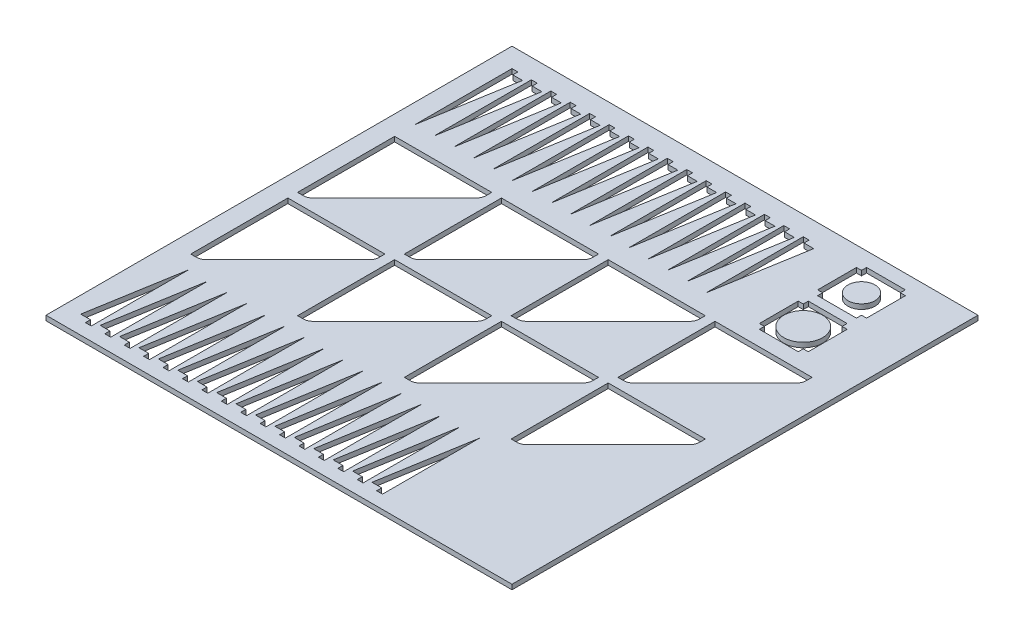
SolidWorks part; units mm, degrees
ref_plane "Front Plane" through (0, 0, 0) normal (0, 0, 1) x (1, 0, 0)
ref_plane "Top Plane" through (0, 0, 0) normal (0, 1, 0) x (1, 0, 0)
ref_plane "Right Plane" through (0, 0, 0) normal (1, 0, 0) x (0, 0, -1)
sketch "Sketch2" plane through (0, 0, 0) normal (0, 1, 0) x (1, 0, 0)
  line L6 (-209.1635, -277.3688) -> (95.6365, -277.3688)
  line L7 (-209.1635, -277.3688) -> (-209.1635, 27.4312)
  line L8 (95.6365, -277.3688) -> (95.6365, 27.4312)
  line L9 (-209.1635, 27.4312) -> (95.6365, 27.4312)
  point P0 (0, 0)
  dimension "D5" = 304.8
  dimension "D6" = 304.8
extrude "Boss-Extrude1" add sketch "Sketch2" along normal blind 3.175
sketch "Sketch3" plane through (0, 3.175, 0) normal (0, 1, 0) x (1, 0, 0)
  line L0 (-196.4635, 14.7312) -> (-196.4635, -48.7688)
  line L1 (-196.4635, -48.7688) -> (-186.3035, 11.4292)
  line L2 (-186.3035, 11.4292) -> (-192.6535, 11.4292)
  line L3 (-192.6535, 11.4292) -> (-192.6535, 14.7312)
  line L4 (-192.6535, 14.7312) -> (-196.4635, 14.7312)
  line L5 (-209.1635, 27.4312) -> (-209.1635, -277.3688) construction
  line L6 (95.6365, 27.4312) -> (-209.1635, 27.4312) construction
  line L7 (-179.9535, 14.7312) -> (-183.7635, 14.7312)
  line L8 (-183.7635, 14.7312) -> (-183.7635, -48.7688)
  line L9 (-183.7635, -48.7688) -> (-173.6035, 11.4292)
  line L10 (-173.6035, 11.4292) -> (-179.9535, 11.4292)
  line L11 (-179.9535, 11.4292) -> (-179.9535, 14.7312)
  line L12 (-167.2535, 14.7312) -> (-171.0635, 14.7312)
  line L13 (-171.0635, 14.7312) -> (-171.0635, -48.7688)
  line L14 (-171.0635, -48.7688) -> (-160.9035, 11.4292)
  line L15 (-160.9035, 11.4292) -> (-167.2535, 11.4292)
  line L16 (-167.2535, 11.4292) -> (-167.2535, 14.7312)
  line L17 (-154.5535, 14.7312) -> (-158.3635, 14.7312)
  line L18 (-158.3635, 14.7312) -> (-158.3635, -48.7688)
  line L19 (-158.3635, -48.7688) -> (-148.2035, 11.4292)
  line L20 (-148.2035, 11.4292) -> (-154.5535, 11.4292)
  line L21 (-154.5535, 11.4292) -> (-154.5535, 14.7312)
  line L22 (-141.8535, 14.7312) -> (-145.6635, 14.7312)
  line L23 (-145.6635, 14.7312) -> (-145.6635, -48.7688)
  line L24 (-145.6635, -48.7688) -> (-135.5035, 11.4292)
  line L25 (-135.5035, 11.4292) -> (-141.8535, 11.4292)
  line L26 (-141.8535, 11.4292) -> (-141.8535, 14.7312)
  line L27 (-129.1535, 14.7312) -> (-132.9635, 14.7312)
  line L28 (-132.9635, 14.7312) -> (-132.9635, -48.7688)
  line L29 (-132.9635, -48.7688) -> (-122.8035, 11.4292)
  line L30 (-122.8035, 11.4292) -> (-129.1535, 11.4292)
  line L31 (-129.1535, 11.4292) -> (-129.1535, 14.7312)
  line L32 (-116.4535, 14.7312) -> (-120.2635, 14.7312)
  line L33 (-120.2635, 14.7312) -> (-120.2635, -48.7688)
  line L34 (-120.2635, -48.7688) -> (-110.1035, 11.4292)
  line L35 (-110.1035, 11.4292) -> (-116.4535, 11.4292)
  line L36 (-116.4535, 11.4292) -> (-116.4535, 14.7312)
  line L37 (-103.7535, 14.7312) -> (-107.5635, 14.7312)
  line L38 (-107.5635, 14.7312) -> (-107.5635, -48.7688)
  line L39 (-107.5635, -48.7688) -> (-97.4035, 11.4292)
  line L40 (-97.4035, 11.4292) -> (-103.7535, 11.4292)
  line L41 (-103.7535, 11.4292) -> (-103.7535, 14.7312)
  line L42 (-91.0535, 14.7312) -> (-94.8635, 14.7312)
  line L43 (-94.8635, 14.7312) -> (-94.8635, -48.7688)
  line L44 (-94.8635, -48.7688) -> (-84.7035, 11.4292)
  line L45 (-84.7035, 11.4292) -> (-91.0535, 11.4292)
  line L46 (-91.0535, 11.4292) -> (-91.0535, 14.7312)
  line L47 (-78.3535, 14.7312) -> (-82.1635, 14.7312)
  line L48 (-82.1635, 14.7312) -> (-82.1635, -48.7688)
  line L49 (-82.1635, -48.7688) -> (-72.0035, 11.4292)
  line L50 (-72.0035, 11.4292) -> (-78.3535, 11.4292)
  line L51 (-78.3535, 11.4292) -> (-78.3535, 14.7312)
  line L52 (-65.6535, 14.7312) -> (-69.4635, 14.7312)
  line L53 (-69.4635, 14.7312) -> (-69.4635, -48.7688)
  line L54 (-69.4635, -48.7688) -> (-59.3035, 11.4292)
  line L55 (-59.3035, 11.4292) -> (-65.6535, 11.4292)
  line L56 (-65.6535, 11.4292) -> (-65.6535, 14.7312)
  line L57 (-52.9535, 14.7312) -> (-56.7635, 14.7312)
  line L58 (-56.7635, 14.7312) -> (-56.7635, -48.7688)
  line L59 (-56.7635, -48.7688) -> (-46.6035, 11.4292)
  line L60 (-46.6035, 11.4292) -> (-52.9535, 11.4292)
  line L61 (-52.9535, 11.4292) -> (-52.9535, 14.7312)
  line L62 (-40.2535, 14.7312) -> (-44.0635, 14.7312)
  line L63 (-44.0635, 14.7312) -> (-44.0635, -48.7688)
  line L64 (-44.0635, -48.7688) -> (-33.9035, 11.4292)
  line L65 (-33.9035, 11.4292) -> (-40.2535, 11.4292)
  line L66 (-40.2535, 11.4292) -> (-40.2535, 14.7312)
  line L67 (-27.5535, 14.7312) -> (-31.3635, 14.7312)
  line L68 (-31.3635, 14.7312) -> (-31.3635, -48.7688)
  line L69 (-31.3635, -48.7688) -> (-21.2035, 11.4292)
  line L70 (-21.2035, 11.4292) -> (-27.5535, 11.4292)
  line L71 (-27.5535, 11.4292) -> (-27.5535, 14.7312)
  line L72 (-14.8535, 14.7312) -> (-18.6635, 14.7312)
  line L73 (-18.6635, 14.7312) -> (-18.6635, -48.7688)
  line L74 (-18.6635, -48.7688) -> (-8.5035, 11.4292)
  line L75 (-8.5035, 11.4292) -> (-14.8535, 11.4292)
  line L76 (-14.8535, 11.4292) -> (-14.8535, 14.7312)
  line L77 (-2.1535, 14.7312) -> (-5.9635, 14.7312)
  line L78 (-5.9635, 14.7312) -> (-5.9635, -48.7688)
  line L79 (-5.9635, -48.7688) -> (4.1965, 11.4292)
  line L80 (4.1965, 11.4292) -> (-2.1535, 11.4292)
  line L81 (-2.1535, 11.4292) -> (-2.1535, 14.7312)
  line L326 (-133.5339, -68.3803) -> (-132.9635, -68.3803)
  line L328 (32.1365, 14.7312) -> (28.8345, 14.7312)
  line L329 (32.1365, -10.6688) -> (28.8345, -10.6688)
  line L330 (28.8345, 14.7312) -> (28.8345, -10.6688)
  line L331 (-196.4635, -62.0303) -> (-132.9635, -62.0303)
  line L333 (32.1365, 14.7312) -> (32.1365, 18.0332)
  line L334 (57.5365, 14.7312) -> (57.5365, 18.0332)
  line L335 (32.1365, 18.0332) -> (57.5365, 18.0332)
  line L336 (32.1365, -10.6688) -> (32.1365, -13.9708)
  line L337 (57.5365, -13.9708) -> (32.1365, -13.9708)
  line L338 (57.5365, -10.6688) -> (57.5365, -13.9708)
  line L339 (-196.4635, -62.0303) -> (-196.4635, -125.5303)
  line L340 (57.5365, 14.7312) -> (60.8385, 14.7312)
  line L341 (60.8385, -10.6688) -> (60.8385, 14.7312)
  line L342 (57.5365, -10.6688) -> (60.8385, -10.6688)
  line L343 (-196.4635, -125.5303) -> (-192.7438, -125.5303)
  line L352 (57.5365, -52.0708) -> (32.1365, -52.0708)
  line L353 (57.5365, -52.0708) -> (57.5365, -48.7688)
  line L354 (32.1365, -20.0668) -> (57.5365, -20.0668)
  line L355 (60.8385, -48.7688) -> (60.8385, -23.3688)
  line L356 (57.5365, -48.7688) -> (60.8385, -48.7688)
  line L357 (-132.9635, -62.0303) -> (-132.9635, -65.7501)
  line L359 (32.1365, -23.3688) -> (32.1365, -20.0668)
  line L361 (-190.1135, -124.96) -> (-190.1135, -125.5303)
  line L362 (32.1365, -48.7688) -> (28.8345, -48.7688)
  line L363 (32.1365, -48.7688) -> (32.1365, -52.0708)
  line L364 (-190.1135, -68.3803) -> (-139.3135, -68.3803) construction
  line L365 (-10.4536, -205.1954) -> (-20.6136, -265.3934)
  line L366 (-190.1135, -68.3803) -> (-190.1135, -119.1803) construction
  line L367 (-134.8234, -70.2402) -> (-188.2536, -123.6705)
  line L368 (-196.4635, -125.5303) -> (-132.9635, -125.5303) construction
  line L369 (-132.9635, -62.0303) -> (-132.9635, -125.5303) construction
  line L370 (-126.6135, -125.5303) -> (-122.8938, -125.5303)
  line L371 (57.5365, -23.3688) -> (60.8385, -23.3688)
  line L372 (-126.6135, -62.0303) -> (-126.6135, -125.5303)
  line L373 (-126.6135, -62.0303) -> (-63.1135, -62.0303)
  line L374 (32.1365, -23.3688) -> (28.8345, -23.3688)
  line L375 (57.5365, -23.3688) -> (57.5365, -20.0668)
  line L376 (-63.1135, -62.0303) -> (-63.1135, -65.7501)
  line L377 (28.8345, -23.3688) -> (28.8345, -48.7688)
  line L378 (-139.3135, -68.3803) -> (-139.3135, -119.1803) construction
  line L379 (-190.1135, -119.1803) -> (-139.3135, -119.1803) construction
  line L380 (-64.9734, -70.2402) -> (-118.4036, -123.6705)
  line L381 (-56.7635, -125.5303) -> (-53.0438, -125.5303)
  line L382 (-56.7635, -62.0303) -> (-56.7635, -125.5303)
  line L383 (-56.7635, -62.0303) -> (6.7365, -62.0303)
  line L384 (6.7365, -62.0303) -> (6.7365, -65.7501)
  line L385 (4.8766, -70.2402) -> (-48.5536, -123.6705)
  line L386 (13.0865, -125.5303) -> (16.8062, -125.5303)
  line L387 (13.0865, -62.0303) -> (13.0865, -125.5303)
  line L388 (13.0865, -62.0303) -> (76.5865, -62.0303)
  line L389 (76.5865, -62.0303) -> (76.5865, -65.7501)
  line L390 (74.7266, -70.2402) -> (21.2964, -123.6705)
  line L391 (76.5865, -131.8803) -> (76.5865, -135.6001)
  line L392 (-134.8234, -140.0902) -> (-188.2536, -193.5205)
  line L393 (-126.6135, -131.8803) -> (-63.1135, -131.8803)
  line L394 (-56.7635, -195.3803) -> (-53.0438, -195.3803)
  line L395 (-126.6135, -195.3803) -> (-122.8938, -195.3803)
  line L396 (-126.6135, -131.8803) -> (-126.6135, -195.3803)
  line L397 (-56.7635, -131.8803) -> (-56.7635, -195.3803)
  line L398 (13.0865, -195.3803) -> (16.8062, -195.3803)
  line L399 (-63.1135, -131.8803) -> (-63.1135, -135.6001)
  line L400 (4.8766, -140.0902) -> (-48.5536, -193.5205)
  line L401 (74.7266, -140.0902) -> (21.2964, -193.5205)
  line L402 (-132.9635, -131.8803) -> (-132.9635, -135.6001)
  line L403 (6.7365, -131.8803) -> (6.7365, -135.6001)
  line L404 (-196.4635, -131.8803) -> (-196.4635, -195.3803)
  line L405 (-196.4635, -195.3803) -> (-192.7438, -195.3803)
  line L406 (-64.9734, -140.0902) -> (-118.4036, -193.5205)
  line L407 (-56.7635, -131.8803) -> (6.7365, -131.8803)
  line L408 (13.0865, -131.8803) -> (13.0865, -195.3803)
  line L409 (-196.4635, -131.8803) -> (-132.9635, -131.8803)
  line L410 (13.0865, -131.8803) -> (76.5865, -131.8803)
  line L411 (-90.4636, -265.3934) -> (-90.4636, -268.6954)
  line L412 (-192.0636, -268.6954) -> (-188.2536, -268.6954)
  line L413 (-52.3636, -265.3934) -> (-52.3636, -268.6954)
  line L414 (-73.9536, -205.1954) -> (-84.1136, -265.3934)
  line L415 (-103.1636, -268.6954) -> (-99.3536, -268.6954)
  line L416 (-153.9636, -268.6954) -> (-150.1536, -268.6954)
  line L417 (-48.5536, -205.1954) -> (-58.7136, -265.3934)
  line L418 (-86.6536, -268.6954) -> (-86.6536, -205.1954)
  line L419 (-99.3536, -205.1954) -> (-109.5136, -265.3934)
  line L420 (-134.9136, -265.3934) -> (-128.5636, -265.3934)
  line L421 (-166.6636, -268.6954) -> (-162.8536, -268.6954)
  line L422 (-175.5536, -205.1954) -> (-185.7136, -265.3934)
  line L423 (-1.5636, -265.3934) -> (-1.5636, -268.6954)
  line L424 (-35.8536, -268.6954) -> (-35.8536, -205.1954)
  line L425 (-73.9536, -268.6954) -> (-73.9536, -205.1954)
  line L426 (-99.3536, -268.6954) -> (-99.3536, -205.1954)
  line L427 (-162.8536, -205.1954) -> (-173.0136, -265.3934)
  line L428 (-14.2636, -268.6954) -> (-10.4536, -268.6954)
  line L429 (-23.1536, -268.6954) -> (-23.1536, -205.1954)
  line L430 (-112.0536, -205.1954) -> (-122.2136, -265.3934)
  line L431 (-150.1536, -205.1954) -> (-160.3136, -265.3934)
  line L432 (-160.3136, -265.3934) -> (-153.9636, -265.3934)
  line L433 (-175.5536, -268.6954) -> (-175.5536, -205.1954)
  line L434 (-20.6136, -265.3934) -> (-14.2636, -265.3934)
  line L435 (-58.7136, -265.3934) -> (-52.3636, -265.3934)
  line L436 (-122.2136, -265.3934) -> (-115.8636, -265.3934)
  line L437 (-162.8536, -268.6954) -> (-162.8536, -205.1954)
  line L438 (-166.6636, -265.3934) -> (-166.6636, -268.6954)
  line L439 (2.2464, -268.6954) -> (2.2464, -205.1954)
  line L440 (-77.7636, -265.3934) -> (-77.7636, -268.6954)
  line L441 (-109.5136, -265.3934) -> (-103.1636, -265.3934)
  line L442 (-137.4536, -205.1954) -> (-147.6136, -265.3934)
  line L443 (2.2464, -205.1954) -> (-7.9136, -265.3934)
  line L444 (-61.2536, -205.1954) -> (-71.4136, -265.3934)
  line L445 (-179.3636, -268.6954) -> (-175.5536, -268.6954)
  line L446 (-1.5636, -268.6954) -> (2.2464, -268.6954)
  line L447 (-26.9636, -268.6954) -> (-23.1536, -268.6954)
  line L448 (-35.8536, -205.1954) -> (-46.0136, -265.3934)
  line L449 (-115.8636, -265.3934) -> (-115.8636, -268.6954)
  line L450 (-150.1536, -268.6954) -> (-150.1536, -205.1954)
  line L451 (-10.4536, -268.6954) -> (-10.4536, -205.1954)
  line L452 (-26.9636, -265.3934) -> (-26.9636, -268.6954)
  line L453 (-90.4636, -268.6954) -> (-86.6536, -268.6954)
  line L454 (-185.7136, -265.3934) -> (-179.3636, -265.3934)
  line L455 (-179.3636, -265.3934) -> (-179.3636, -268.6954)
  line L456 (-188.2536, -205.1954) -> (-198.4136, -265.3934)
  line L457 (-14.2636, -265.3934) -> (-14.2636, -268.6954)
  line L458 (-33.3136, -265.3934) -> (-26.9636, -265.3934)
  line L459 (-137.4536, -268.6954) -> (-137.4536, -205.1954)
  line L460 (-153.9636, -265.3934) -> (-153.9636, -268.6954)
  line L461 (-52.3636, -268.6954) -> (-48.5536, -268.6954)
  line L462 (-48.5536, -268.6954) -> (-48.5536, -205.1954)
  line L463 (-84.1136, -265.3934) -> (-77.7636, -265.3934)
  line L464 (-103.1636, -265.3934) -> (-103.1636, -268.6954)
  line L465 (-147.6136, -265.3934) -> (-141.2636, -265.3934)
  line L466 (-86.6536, -205.1954) -> (-96.8136, -265.3934)
  line L467 (-115.8636, -268.6954) -> (-112.0536, -268.6954)
  line L468 (-124.7536, -268.6954) -> (-124.7536, -205.1954)
  line L469 (-198.4136, -265.3934) -> (-192.0636, -265.3934)
  line L470 (-46.0136, -265.3934) -> (-39.6636, -265.3934)
  line L471 (-65.0636, -265.3934) -> (-65.0636, -268.6954)
  line L472 (-77.7636, -268.6954) -> (-73.9536, -268.6954)
  line L473 (-96.8136, -265.3934) -> (-90.4636, -265.3934)
  line L474 (-141.2636, -268.6954) -> (-137.4536, -268.6954)
  line L475 (-173.0136, -265.3934) -> (-166.6636, -265.3934)
  line L476 (-39.6636, -265.3934) -> (-39.6636, -268.6954)
  line L477 (-61.2536, -268.6954) -> (-61.2536, -205.1954)
  line L478 (-71.4136, -265.3934) -> (-65.0636, -265.3934)
  line L479 (-112.0536, -268.6954) -> (-112.0536, -205.1954)
  line L480 (-128.5636, -265.3934) -> (-128.5636, -268.6954)
  line L481 (-188.2536, -268.6954) -> (-188.2536, -205.1954)
  line L482 (-192.0636, -265.3934) -> (-192.0636, -268.6954)
  line L483 (-7.9136, -265.3934) -> (-1.5636, -265.3934)
  line L484 (-39.6636, -268.6954) -> (-35.8536, -268.6954)
  line L485 (-65.0636, -268.6954) -> (-61.2536, -268.6954)
  line L486 (-23.1536, -205.1954) -> (-33.3136, -265.3934)
  line L487 (-128.5636, -268.6954) -> (-124.7536, -268.6954)
  line L488 (-124.7536, -205.1954) -> (-134.9136, -265.3934)
  line L489 (-141.2636, -265.3934) -> (-141.2636, -268.6954)
  circle A0 centre (44.8365, 2.0312) radius 8.89
  circle A1 centre (44.8365, -36.0688) radius 12.7
  arc A2 (-132.9635, -65.7501) -> (-134.8234, -70.2402) centre (-139.3135, -65.7501) cw
  arc A3 (-192.7438, -125.5303) -> (-188.2536, -123.6705) centre (-192.7438, -119.1803) ccw
  arc A4 (-122.8938, -125.5303) -> (-118.4036, -123.6705) centre (-122.8938, -119.1803) ccw
  arc A5 (-63.1135, -65.7501) -> (-64.9734, -70.2402) centre (-69.4635, -65.7501) cw
  arc A6 (-53.0438, -125.5303) -> (-48.5536, -123.6705) centre (-53.0438, -119.1803) ccw
  arc A7 (6.7365, -65.7501) -> (4.8766, -70.2402) centre (0.3865, -65.7501) cw
  arc A8 (16.8062, -125.5303) -> (21.2964, -123.6705) centre (16.8062, -119.1803) ccw
  arc A9 (76.5865, -65.7501) -> (74.7266, -70.2402) centre (70.2365, -65.7501) cw
  arc A10 (6.7365, -135.6001) -> (4.8766, -140.0902) centre (0.3865, -135.6001) cw
  arc A11 (-63.1135, -135.6001) -> (-64.9734, -140.0902) centre (-69.4635, -135.6001) cw
  arc A12 (-122.8938, -195.3803) -> (-118.4036, -193.5205) centre (-122.8938, -189.0303) ccw
  arc A13 (16.8062, -195.3803) -> (21.2964, -193.5205) centre (16.8062, -189.0303) ccw
  arc A14 (76.5865, -135.6001) -> (74.7266, -140.0902) centre (70.2365, -135.6001) cw
  arc A15 (-132.9635, -135.6001) -> (-134.8234, -140.0902) centre (-139.3135, -135.6001) cw
  arc A16 (-53.0438, -195.3803) -> (-48.5536, -193.5205) centre (-53.0438, -189.0303) ccw
  arc A17 (-192.7438, -195.3803) -> (-188.2536, -193.5205) centre (-192.7438, -189.0303) ccw
  dimension "D24" = 17.78
  dimension "D25" = 25.4
  dimension "D14" = 6.35
  dimension "D15" = 6.35
  dimension "D1" = 63.5
  dimension "D2" = 3.302
  dimension "D3" = 6.35
  dimension "D4" = 3.81
  dimension "D5" = 12.7
  dimension "D6" = 12.7
  dimension "D11" = 63.5
  dimension "D12" = 63.5
  dimension "D13" = 6.35
  dimension "D16" = 4
  dimension "D17" = 25.4
  dimension "D21" = 3.302
  dimension "D22" = 3.302
  dimension "D23" = 3.302
  dimension "D7" = 16
extrude "Cut-Extrude1" cut sketch "Sketch3" against normal through all both and the other way through all contours L338 L342 L341 L340 L334 L335 L333 L328 L330 L329 L336 L337 A0 | L374 L377 L362 L363 L352 L353 L356 L355 L371 L375 L354 L359 A1 | L1 L2 L3 L4 L0 | L443 L483 L423 L446 L439 | L8 L9 L10 L11 L7 | L365 L434 L457 L428 L451 | L13 L14 L15 L16 L12 | L486 L458 L452 L447 L429 | L18 L19 L20 L21 L17 | L448 L470 L476 L484 L424 | L23 L24 L25 L26 L22 | L417 L435 L413 L461 L462 | L28 L29 L30 L31 L27 | L444 L478 L471 L485 L477 | L33 L34 L35 L36 L32 | L414 L463 L440 L472 L425 | L38 L39 L40 L41 L37 | L466 L473 L411 L453 L418 | L43 L44 L45 L46 L42 | L419 L441 L464 L415 L426 | L48 L49 L50 L51 L47 | L430 L436 L449 L467 L479 | L53 L54 L55 L56 L52 | L488 L420 L480 L487 L468 | L58 L59 L60 L61 L57 | L442 L465 L489 L474 L459 | L63 L64 L65 L66 L62 | L431 L432 L460 L416 L450 | L68 L69 L70 L71 L67 | L427 L475 L438 L421 L437 | L73 L74 L75 L76 L72 | L422 L454 L455 L445 L433 | L78 L79 L80 L81 L77 | L456 L469 L482 L412 L481 | L331 L357 A2 L367 A3 L343 L339 | L373 L376 A5 L380 A4 L370 L372 | L383 L384 A7 L385 A6 L381 L382 | L388 L389 A9 L390 A8 L386 L387 | L402 A15 L392 A17 L405 L404 L409 | L393 L399 A11 L406 A12 L395 L396 | L407 L403 A10 L400 A16 L394 L397 | L410 L391 A14 L401 A13 L398 L408
